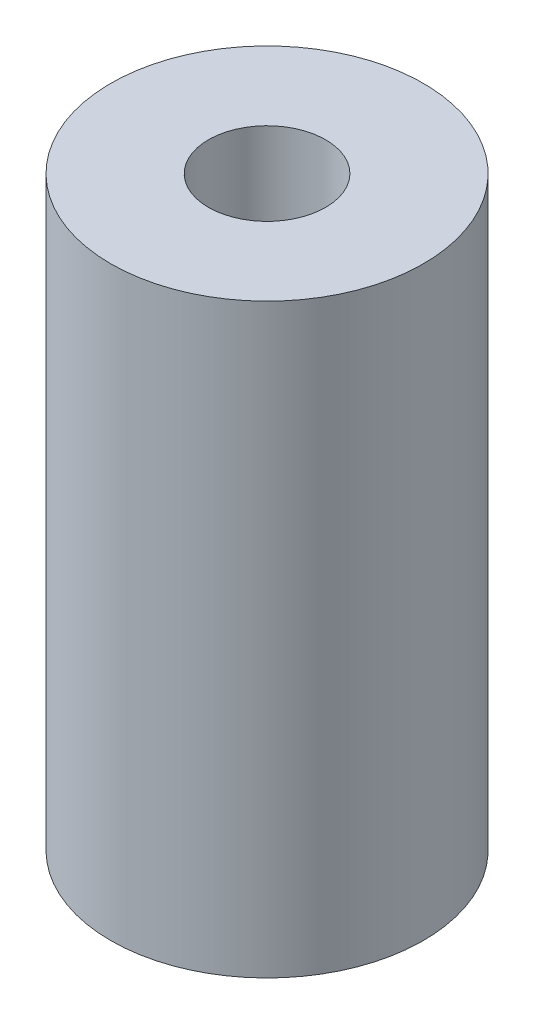
SolidWorks part; units mm, degrees
ref_plane "Front Plane" through (0, 0, 0) normal (0, 0, 1) x (1, 0, 0)
ref_plane "Top Plane" through (0, 0, 0) normal (0, 1, 0) x (1, 0, 0)
ref_plane "Right Plane" through (0, 0, 0) normal (1, 0, 0) x (0, 0, -1)
sketch "Sketch1" plane through (0, 0, 0) normal (0, 1, 0) x (1, 0, 0)
  circle A0 centre (0, 0) radius 4
  dimension "D1" = 8
extrude "Boss-Extrude1" add sketch "Sketch1" along normal blind 15
sketch "Sketch2" plane through (0, 15, 0) normal (0, 1, 0) x (1, 0, 0)
  circle A0 centre (0, 0) radius 1.5
  dimension "D1" = 3
extrude "Cut-Extrude1" cut sketch "Sketch2" against normal through all
